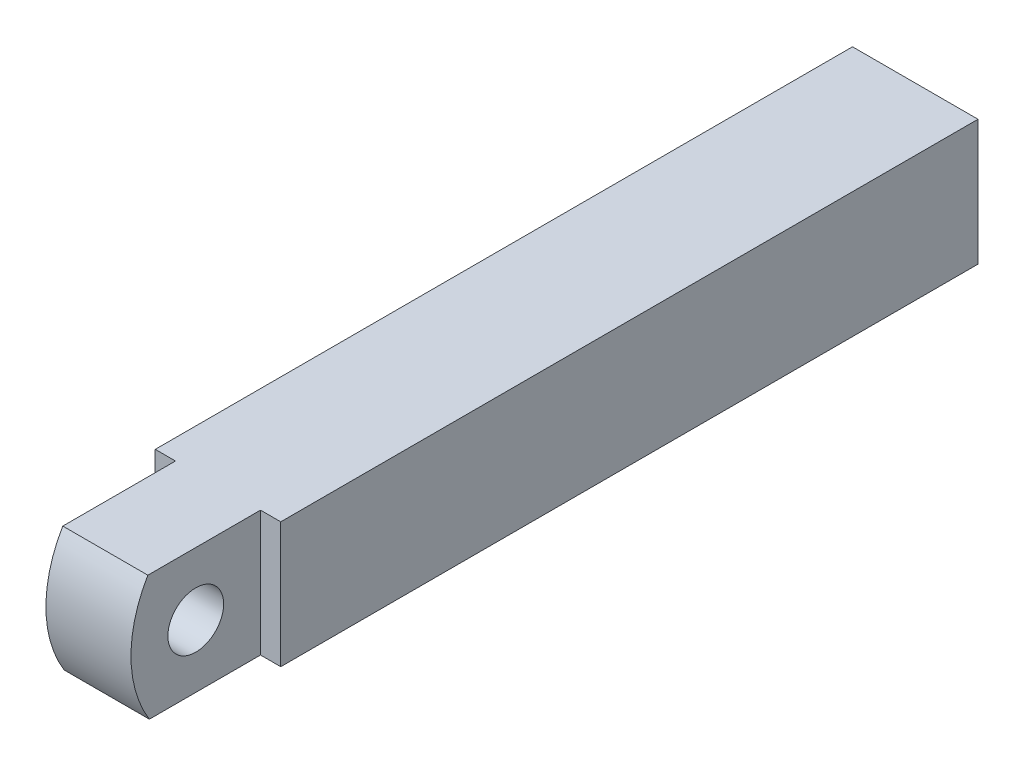
SolidWorks part; units mm, degrees
ref_plane "Plan de face" through (0, 0, 0) normal (0, 0, 1) x (1, 0, 0)
ref_plane "Plan de dessus" through (0, 0, 0) normal (0, 1, 0) x (1, 0, 0)
ref_plane "Plan de droite" through (0, 0, 0) normal (1, 0, 0) x (0, 0, -1)
sketch "Esquisse1" plane through (0, 0, 0) normal (0, 0, 1) x (1, 0, 0)
  line L1 (-4.5, 4.5) -> (4.5, 4.5)
  line L2 (-4.5, 4.5) -> (-4.5, -4.5)
  line L3 (-4.5, -4.5) -> (4.5, -4.5)
  line L4 (4.5, 4.5) -> (4.5, -4.5)
  line L5 (-4.5, 4.5) -> (4.5, -4.5) construction
  line L6 (-4.5, -4.5) -> (4.5, 4.5) construction
  point P0 (0, 0)
  dimension "D1" = 9
  dimension "D2" = 9
extrude "Boss.-Extru.1" add sketch "Esquisse1" along normal blind 50
sketch "Esquisse2" plane through (4.5, 0, 0) normal (1, 0, 0) x (0, 0, -1)
  line L1 (-59.29, 4.5) -> (-50, 4.5)
  line L2 (-59.29, 4.5) -> (-59.29, -4.5)
  line L3 (-59.29, -4.5) -> (-50, -4.5)
  line L4 (-50, 4.5) -> (-50, -4.5)
  line L5 (-59.29, 4.5) -> (-50, -4.5) construction
  line L6 (-59.29, -4.5) -> (-50, 4.5) construction
  circle A0 centre (-54.645, 0) radius 2
  arc A1 (-57.9709, -4.5) -> (-58.0805, 4.5) centre (-50.645, 0.0899) cw
  point P0 (-54.645, 0)
  point P11 (0, 0)
  dimension "D2" = 4
  dimension "D1" = 9.29
  dimension "D3" = 4
extrude "Boss.-Extru.3" add sketch "Esquisse2" against normal blind 6.1 from offset 1.45 offset against normal yes
